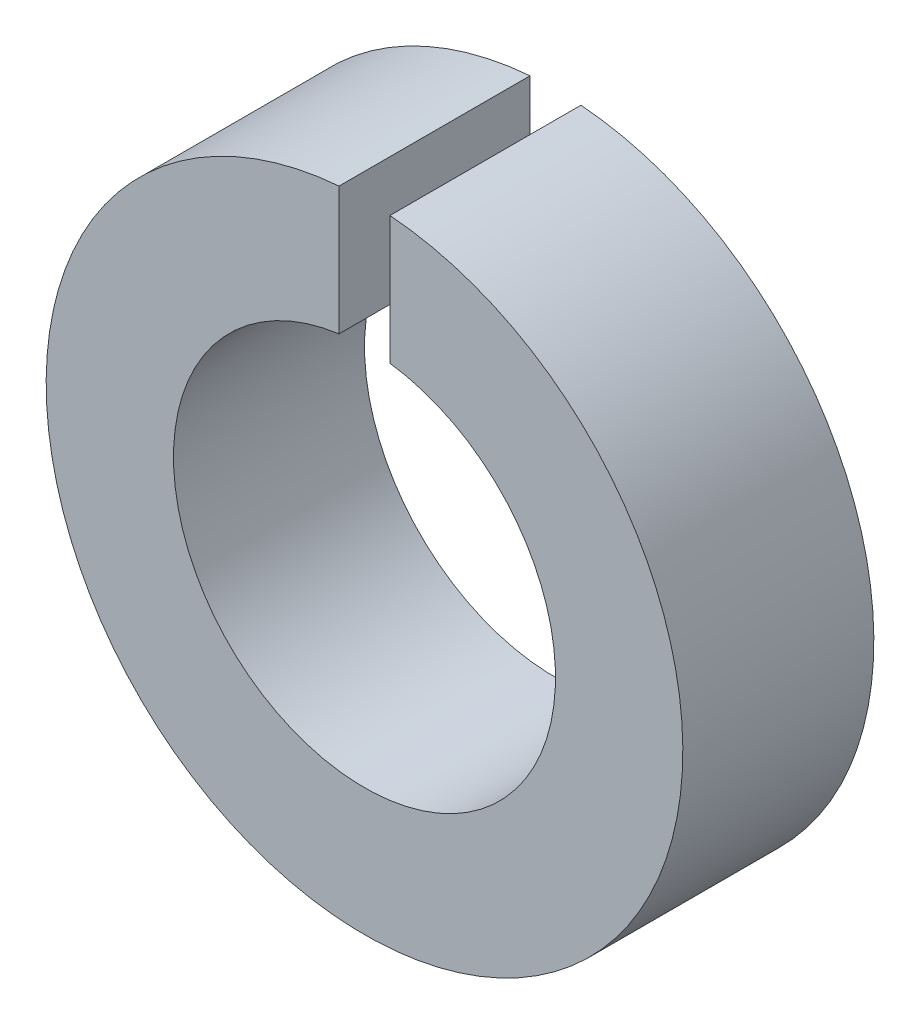
SolidWorks part; units mm, degrees
ref_plane "Front Plane" through (0, 0, 0) normal (0, 0, 1) x (1, 0, 0)
ref_plane "Top Plane" through (0, 0, 0) normal (0, 1, 0) x (1, 0, 0)
ref_plane "Right Plane" through (0, 0, 0) normal (1, 0, 0) x (0, 0, -1)
sketch "Sketch1" plane through (0, 0, 0) normal (0, 0, 1) x (1, 0, 0)
  line L0 (0, -26.4532) -> (0, 26.4532) construction
  line L1 (-33.2488, 0) -> (33.2488, 0) construction
  line L2 (1.27, 9.44) -> (1.27, 15.8241)
  line L3 (-1.27, 9.44) -> (-1.27, 15.8241)
  arc A0 (-1.27, 9.44) -> (1.27, 9.44) centre (0, 0) ccw
  arc A2 (-1.27, 15.8241) -> (1.27, 15.8241) centre (0, 0) ccw
  circle A4 centre (0, 0) radius 9.525 construction
  circle A5 centre (0, 0) radius 15.875 construction
  point P1 (15.875, 0)
  point P7 (0, 0)
  point P11 (0, 0)
  point P13 (9.1088, 2.7848)
  dimension "D1" = 19.05
  dimension "D3" = 1.27
  dimension "D4" = 1.27
  dimension "D2" = 6.35
extrude "Boss-Extrude2" add sketch "Sketch1" along normal mid plane 9.525
